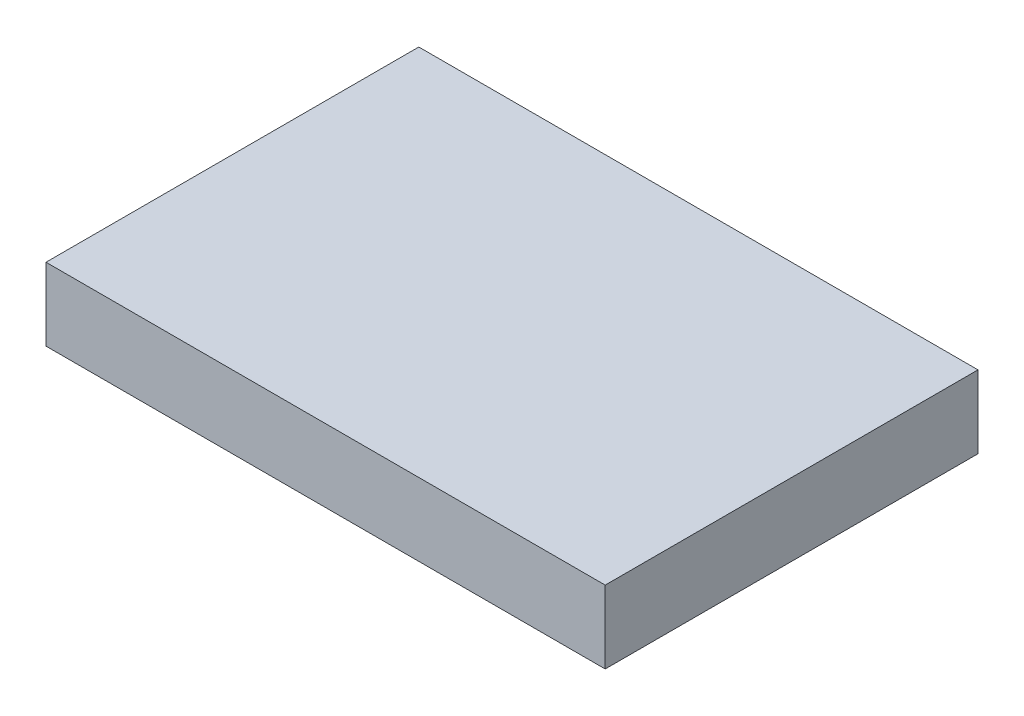
SolidWorks part; units mm, degrees
ref_plane "Front Plane" through (0, 0, 0) normal (0, 0, 1) x (1, 0, 0)
ref_plane "Top Plane" through (0, 0, 0) normal (0, 1, 0) x (1, 0, 0)
ref_plane "Right Plane" through (0, 0, 0) normal (1, 0, 0) x (0, 0, -1)
sketch "Sketch1" plane through (0, 0, 0) normal (0, 1, 0) x (1, 0, 0)
  line L1 (-11.925, -7.95) -> (11.925, -7.95)
  line L2 (-11.925, -7.95) -> (-11.925, 7.95)
  line L3 (-11.925, 7.95) -> (11.925, 7.95)
  line L4 (11.925, -7.95) -> (11.925, 7.95)
  line L5 (-11.925, -7.95) -> (11.925, 7.95) construction
  line L6 (-11.925, 7.95) -> (11.925, -7.95) construction
  point P0 (0, 0)
  dimension "D1" = 15.9
  dimension "D2" = 23.85
extrude "Boss-Extrude1" add sketch "Sketch1" along normal blind 3.1
shell "Shell1" thickness 1.2
sketch "Sketch2" plane through (0, 1.9, 0) normal (0, -1, 0) x (1, 0, 0)
  line L0 (11.925, 7.95) -> (11.925, -7.95) construction
  line L1 (11.925, -7.95) -> (-11.925, -7.95) construction
  circle A0 centre (3.975, 0) radius 3.2
  circle A1 centre (3.975, 0) radius 2.4
  point P9 (-8.2515, 4.2459)
  point P10 (0, -4.0328)
  point P11 (0, 0)
  dimension "D1" = 6.4
  dimension "D2" = 4.8
  dimension "D3" = 7.95
  dimension "D4" = 7.95
extrude "Boss-Extrude2" add sketch "Sketch2" along normal up to surface (1.9 mm away) up to face at (0, 0, 0)
pattern_linear "LPattern1" count 2 spacing 8 along (-1, 0, 0) of "Boss-Extrude2"
equation "\"3..10mm\"=3"
